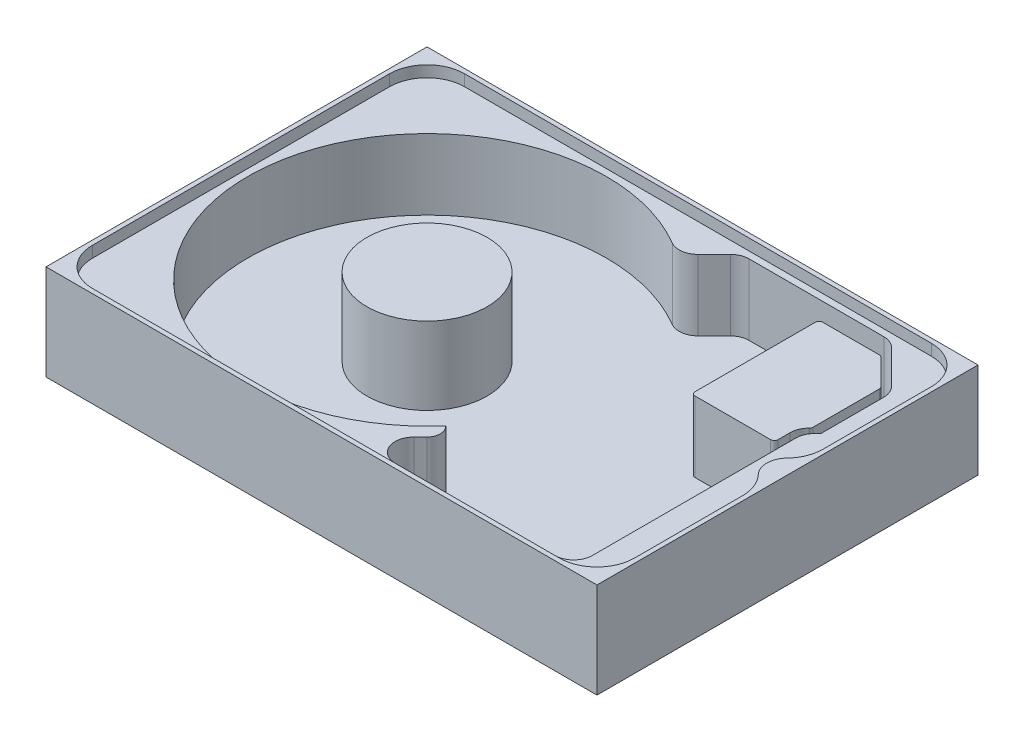
SolidWorks part; units mm, degrees
material "Plain Carbon Steel"
ref_plane "Front Plane" through (0, 0, 0) normal (0, 0, 1) x (1, 0, 0)
ref_plane "Top Plane" through (0, 0, 0) normal (0, 1, 0) x (1, 0, 0)
ref_plane "Right Plane" through (0, 0, 0) normal (1, 0, 0) x (0, 0, -1)
sketch "Sketch1" plane through (0, 0, 0) normal (0, 1, 0) x (1, 0, 0)
  line L1 (-73.325, 50.71) -> (73.325, 50.71)
  line L2 (-73.325, 50.71) -> (-73.325, -50.71)
  line L3 (-73.325, -50.71) -> (73.325, -50.71)
  line L4 (73.325, 50.71) -> (73.325, -50.71)
  line L5 (-73.325, 50.71) -> (73.325, -50.71) construction
  line L6 (-73.325, -50.71) -> (73.325, 50.71) construction
  point P0 (0, 0)
  dimension "D1" = 146.65
  dimension "D2" = 101.42
extrude "Boss-Extrude1" add sketch "Sketch1" along normal blind 25.4
sketch "Sketch2" plane through (0, 25.4, 0) normal (0, 1, 0) x (1, 0, 0)
  line L10 (73.325, -50.71) -> (73.325, 50.71) construction
  line L14 (-72.125, -49.51) -> (72.125, -49.51)
  line L15 (72.125, -49.51) -> (72.125, 49.51)
  line L16 (72.125, 49.51) -> (-72.125, 49.51)
  line L17 (-72.125, 49.51) -> (-72.125, -49.51)
  line L18 (-72.125, -49.51) -> (72.125, -49.51)
  line L19 (72.125, -49.51) -> (72.125, 49.51)
  line L20 (72.125, 49.51) -> (-72.125, 49.51)
  line L21 (-72.125, 49.51) -> (-72.125, -49.51)
  arc A0 (72.125, 5.3675) -> (72.125, -5.3675) centre (73.325, 0) ccw
  dimension "D2" = 11
  dimension "D1" = 1.2
extrude "Cut-Extrude1" cut sketch "Sketch2" against normal blind 3 contours A0 L19 L20 L21 L18
fillet "Fillet1" radius 10 6 edges at (72.125, 23.9, -5.3675) (72.125, 23.9, 5.3675) (-72.125, 23.9, 49.51) (72.125, 23.9, 49.51) (72.125, 23.9, -49.51) (-72.125, 23.9, -49.51)
sketch "Sketch3" plane through (0, 22.4, 0) normal (0, 1, 0) x (1, 0, 0)
  line L0 (-73.325, 0) -> (73.325, 0) construction
  line L1 (-73.325, 50.71) -> (-73.325, -50.71) construction
  line L2 (73.325, -50.71) -> (73.325, 50.71) construction
  line L3 (-22.615, 47.7) -> (-73.325, 47.7) construction
  line L4 (-70.315, 0) -> (-70.315, 50.71) construction
  line L5 (73.325, 50.71) -> (-73.325, 50.71) construction
  line L6 (62.925, -46.51) -> (3.325, -46.51)
  line L7 (62.925, -46.51) -> (62.925, 14.7)
  line L8 (-73.325, -50.71) -> (73.325, -50.71) construction
  line L9 (65.225, 17) -> (65.225, 35.8)
  line L10 (65.225, 35.8) -> (53.325, 47.7)
  line L11 (53.325, 47.7) -> (13.325, 47.7)
  line L12 (65.225, 17) -> (62.925, 14.7)
  line L13 (13.325, 47.7) -> (4.7175, 39.0925)
  line L14 (3.325, -46.51) -> (13.61, -36.225)
  line L15 (13.61, -36.225) -> (11.114, -33.729) construction
  circle A0 centre (-22.615, 0) radius 47.7
  arc A1 (13.61, -36.225) -> (13.5159, -31.1423) centre (11.114, -33.729) ccw
  dimension "D1" = 95.4
  dimension "D2" = 4.2
  dimension "D3" = 10.4
  dimension "D4" = 8.1
  dimension "D5" = 45
  dimension "D6" = 3.01
  dimension "D7" = 20
  dimension "D8" = 17
  dimension "D9" = 45
  dimension "D10" = 60
  dimension "D11" = 70
  dimension "D12" = 45
extrude "Cut-Extrude2" cut sketch "Sketch3" against normal blind 18.8 contours A1 L14 L6 L7 L12 L9 L10 L11 L13 A0 | A0
fillet "Fillet2" radius 5 7 edges at (3.325, 13, 46.51) (62.925, 13, 46.51) (62.925, 13, -14.7) (65.225, 13, -35.8) (53.325, 13, -47.7) (13.325, 13, -47.7) (4.7175, 13, -39.0925)
sketch "Sketch4" plane through (0, 3.6, 0) normal (0, 1, 0) x (1, 0, 0)
  circle A0 centre (-22.615, 0) radius 16
  arc A1 (1.4974, 41.1568) -> (13.5159, -31.1423) centre (-22.615, 0) ccw construction
  dimension "D1" = 32
extrude "Boss-Extrude2" add sketch "Sketch4" along normal blind 20.6
sketch "Sketch5" plane through (0, 3.6, 0) normal (0, 1, 0) x (1, 0, 0)
  line L0 (38.825, 42.9) -> (55.2966, 42.9)
  line L1 (55.2966, 42.9) -> (62.725, 35.4716)
  line L2 (62.725, 35.4716) -> (62.725, 17)
  line L3 (62.725, 17) -> (60.925, 15.2)
  line L4 (60.925, 15.2) -> (60.925, 8.9)
  line L5 (60.925, 8.9) -> (38.825, 8.9)
  line L6 (38.825, 8.9) -> (38.825, 42.9)
  line L7 (65.225, 17) -> (65.225, 33.7289) construction
  line L8 (63.7605, 37.2645) -> (54.7895, 46.2355) construction
  line L9 (62.925, -41.51) -> (62.925, 12.6289) construction
  line L10 (65.225, 17) -> (64.3895, 16.1645) construction
  line L11 (51.2539, 47.7) -> (15.3961, 47.7) construction
  dimension "D1" = 26.4
  dimension "D2" = 2.5
  dimension "D3" = 2
  dimension "D4" = 2
  dimension "D5" = 4.8
  dimension "D6" = 34
extrude "Boss-Extrude3" add sketch "Sketch5" along normal up to surface (18.8 mm away) up to face at (23.5634, 22.4, 0)
fillet "Fillet4" radius 1 6 edges at (38.825, 13, -42.9) (55.2966, 13, -42.9) (62.725, 13, -35.4716) (38.825, 13, -8.9) (60.925, 13, -8.9) (62.725, 13, -17)
fillet "Fillet5" radius 5 1 edges at (60.925, 13, -15.2)
